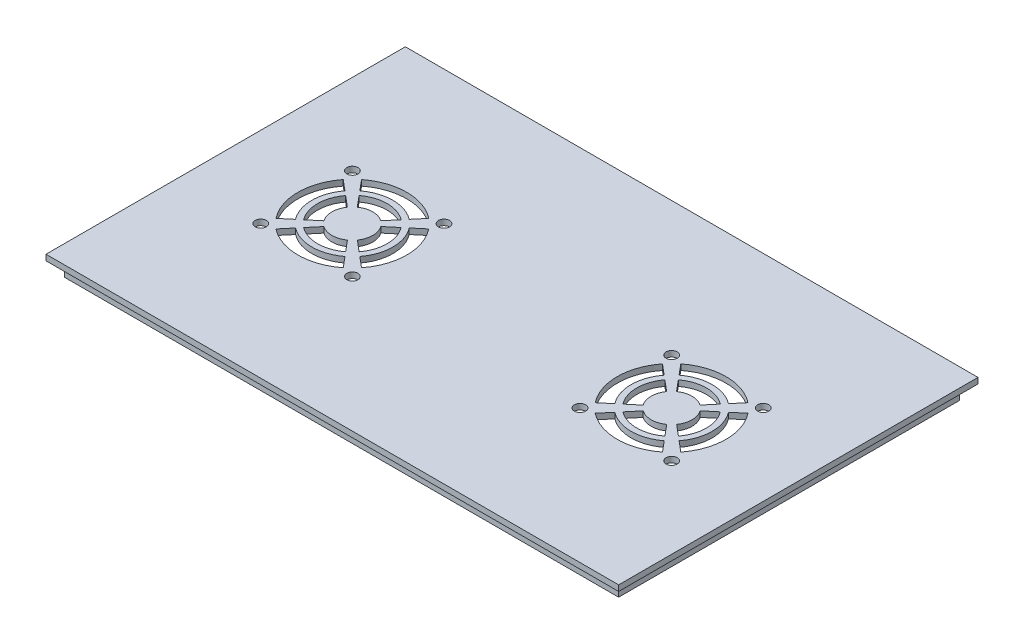
SolidWorks part; units mm, degrees
ref_plane "Front Plane" through (0, 0, 0) normal (0, 0, 1) x (1, 0, 0)
ref_plane "Top Plane" through (0, 0, 0) normal (0, 1, 0) x (1, 0, 0)
ref_plane "Right Plane" through (0, 0, 0) normal (1, 0, 0) x (0, 0, -1)
sketch "Sketch1" plane through (0, 0, 0) normal (0, 1, 0) x (1, 0, 0)
  line L1 (-88.3191, 40.7407) -> (111.6809, 40.7407)
  line L2 (-88.3191, 40.7407) -> (-88.3191, -84.7593)
  line L3 (-88.3191, -84.7593) -> (111.6809, -84.7593)
  line L4 (111.6809, 40.7407) -> (111.6809, -84.7593)
  dimension "D1" = 200
  dimension "D2" = 125.5
extrude "Boss-Extrude1" add sketch "Sketch1" along normal blind 2
sketch "Sketch2" plane through (0, 0, 0) normal (0, -1, 0) x (1, 0, 0)
  line L9 (-85.0691, 81.5093) -> (-85.0691, -37.4907)
  line L10 (-85.0691, -37.4907) -> (108.4309, -37.4907)
  line L11 (108.4309, -37.4907) -> (108.4309, 81.5093)
  line L12 (108.4309, 81.5093) -> (-85.0691, 81.5093)
  line L13 (-85.0691, 81.5093) -> (-85.0691, -37.4907)
  line L14 (-85.0691, -37.4907) -> (108.4309, -37.4907)
  line L15 (108.4309, -37.4907) -> (108.4309, 81.5093)
  line L16 (108.4309, 81.5093) -> (-85.0691, 81.5093)
  dimension "D1" = 3.25
extrude "Boss-Extrude2" add sketch "Sketch2" along normal blind 5
sketch "Sketch3" plane through (0, -5, 0) normal (0, -1, 0) x (1, 0, 0)
  line L20 (105.4309, 78.5093) -> (-82.0691, 78.5093)
  line L21 (-82.0691, 78.5093) -> (-82.0691, -34.4907)
  line L22 (-82.0691, -34.4907) -> (105.4309, -34.4907)
  line L23 (105.4309, -34.4907) -> (105.4309, 78.5093)
  line L24 (105.4309, 78.5093) -> (-82.0691, 78.5093)
  line L25 (-82.0691, 78.5093) -> (-82.0691, -34.4907)
  line L26 (-82.0691, -34.4907) -> (105.4309, -34.4907)
  line L27 (105.4309, -34.4907) -> (105.4309, 78.5093)
  dimension "D1" = 3
extrude "Cut-Extrude1" cut sketch "Sketch3" against normal blind 5
fillet "Fillet1" radius 2 4 edges at (11.6809, 0, -34.4907) (-82.0691, 0, 22.0093) (11.6809, 0, 78.5093) (105.4309, 0, 22.0093)
ref_plane "Plane1" through (11.6809, 0, 0) normal (1, 0, 0) x (0, 0, -1)
hole_wizard "M3.5 Clearance Hole1" positions "Sketch4" profile "Sketch6" hole size "M3.5" standard "ANSI Metric" end condition up to next
sketch "Sketch4" plane through (0, 2, 0) normal (0, -1, 0) x (-1, 0, 0)
  line L0 (88.3191, -84.7593) -> (-111.6809, -84.7593) construction
  line L1 (-111.6809, -84.7593) -> (-111.6809, 40.7407) construction
  line L2 (88.3191, 40.7407) -> (88.3191, -84.7593) construction
  point P0 (60.0691, -38.0093)
  point P3 (28.0691, -38.0093)
  point P5 (28.0691, -6.0093)
  point P7 (60.0691, -6.0093)
  point P9 (-51.4309, -38.0093)
  point P11 (-51.4309, -6.0093)
  point P13 (-83.4309, -6.0093)
  point P15 (-83.4309, -38.0093)
  dimension "D1" = 32
  dimension "D2" = 32
  dimension "D3" = 32
  dimension "D4" = 32
  dimension "D5" = 32
  dimension "D6" = 32
  dimension "D7" = 46.75
  dimension "D8" = 46.75
  dimension "D9" = 28.25
  dimension "D10" = 28.25
sketch "Sketch6" plane through (-60.0691, 2, 38.0093) normal (1, 0, 0) x (0, 0, 1)
  line L0 (0, 0) -> (0, 2)
  line L1 (0, 2) -> (1.95, 2)
  line L2 (1.95, 2) -> (1.95, 0)
  line L5 (1.95, 0) -> (0, 0)
  line L11 (0, -6.35) -> (0, 107.95) construction
  dimension "Thru Hole Dia." = 3.9
  dimension "Thru Hole Depth" = 2
sketch "Sketch9" plane through (0, 2, 0) normal (0, 1, 0) x (1, 0, 0)
  line L0 (-59.0064, -10.2672) -> (-55.293, -13.3888)
  line L1 (-55.2876, -30.6368) -> (-59.0064, -33.7514)
  line L2 (-53.7596, -14.6779) -> (-49.9102, -17.9141)
  line L3 (-49.8975, -26.1224) -> (-53.752, -29.3507)
  line L4 (-52.6966, -10.7907) -> (-55.8112, -7.072)
  line L5 (-32.327, -7.072) -> (-35.4487, -10.7853)
  line L6 (-48.1822, -16.1808) -> (-51.4105, -12.3263)
  line L7 (-36.7378, -12.3187) -> (-39.9739, -16.1682)
  line L8 (-32.8506, -13.3818) -> (-29.1318, -10.2672)
  line L9 (-29.1318, -33.7514) -> (-32.8451, -30.6297)
  line L10 (-38.2406, -17.8961) -> (-34.3862, -14.6679)
  line L11 (-34.3785, -29.3406) -> (-38.228, -26.1045)
  line L12 (-35.4416, -33.2278) -> (-32.327, -36.9466)
  line L13 (-55.8112, -36.9466) -> (-52.6895, -33.2332)
  line L14 (-39.9559, -27.8377) -> (-36.7277, -31.6922)
  line L15 (-51.4004, -31.6998) -> (-48.1643, -27.8503)
  line L16 (-44.0691, -22.0093) -> (-74.1158, -22.0093) construction
  circle A0 centre (-44.0691, -22.0093) radius 19
  circle A1 centre (-28.0691, -38.0093) radius 1.95 construction
  arc A3 (-55.2876, -30.6368) -> (-55.293, -13.3888) centre (-44.0691, -22.0093) cw
  arc A4 (-53.752, -29.3507) -> (-53.7596, -14.6779) centre (-44.0691, -22.0093) cw
  arc A5 (-49.8975, -26.1224) -> (-49.9102, -17.9141) centre (-44.0691, -22.0093) cw
  arc A6 (-59.0064, -33.7514) -> (-59.0064, -10.2672) centre (-44.0691, -22.0093) cw
  arc A7 (-55.8112, -7.072) -> (-32.327, -7.072) centre (-44.0691, -22.0093) cw
  arc A8 (-52.6966, -10.7907) -> (-35.4487, -10.7853) centre (-44.0691, -22.0093) cw
  arc A9 (-51.4105, -12.3263) -> (-36.7378, -12.3187) centre (-44.0691, -22.0093) cw
  arc A10 (-48.1822, -16.1808) -> (-39.9739, -16.1682) centre (-44.0691, -22.0093) cw
  arc A11 (-29.1318, -10.2672) -> (-29.1318, -33.7514) centre (-44.0691, -22.0093) cw
  arc A12 (-32.8506, -13.3818) -> (-32.8451, -30.6297) centre (-44.0691, -22.0093) cw
  arc A13 (-34.3862, -14.6679) -> (-34.3785, -29.3406) centre (-44.0691, -22.0093) cw
  arc A14 (-38.2406, -17.8961) -> (-38.228, -26.1045) centre (-44.0691, -22.0093) cw
  arc A15 (-32.327, -36.9466) -> (-55.8112, -36.9466) centre (-44.0691, -22.0093) cw
  arc A16 (-35.4416, -33.2278) -> (-52.6895, -33.2332) centre (-44.0691, -22.0093) cw
  arc A17 (-36.7277, -31.6922) -> (-51.4004, -31.6998) centre (-44.0691, -22.0093) cw
  arc A18 (-39.9559, -27.8377) -> (-48.1643, -27.8503) centre (-44.0691, -22.0093) cw
  circle A19 centre (-44.0691, -22.0093) radius 7.1336 construction
  point P39 (-44.0691, -22.0093)
  dimension "D1" = 38
  dimension "D2" = 16
  dimension "D3" = 16
  dimension "D4" = 4
  dimension "D5" = 80
  dimension "D6" = 14.2673
extrude "Cut-Extrude3" cut sketch "Sketch9" against normal blind 2 contours L1 A6 L0 A3 | L3 A4 L2 A5 | L4 A7 L5 A8 | L6 A9 L7 A10 | L10 A13 L11 A14 | L8 A11 L9 A12 | L14 A17 L15 A18 | L12 A15 L13 A16
pattern_linear "LPattern1" count 2 spacing 111.5 along (1, 0, 0) of "Cut-Extrude3"
